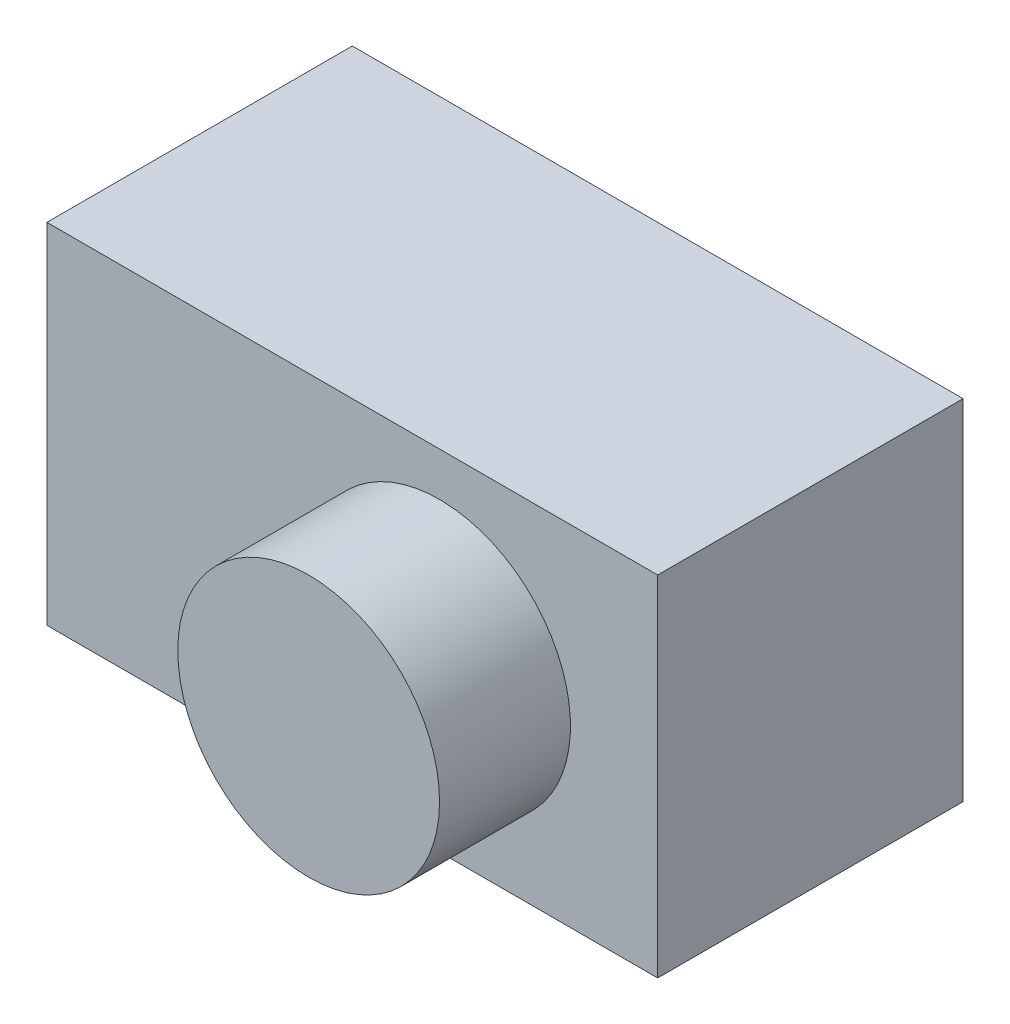
SolidWorks part; units mm, degrees
ref_plane "前视基准面" through (0, 0, 0) normal (0, 0, 1) x (1, 0, 0)
ref_plane "上视基准面" through (0, 0, 0) normal (0, 1, 0) x (1, 0, 0)
ref_plane "右视基准面" through (0, 0, 0) normal (1, 0, 0) x (0, 0, -1)
sketch "草图1" plane through (0, 0, 0) normal (0, 0, 1) x (1, 0, 0)
  line L1 (0, 0) -> (140, 0)
  line L2 (0, 0) -> (0, 80)
  line L3 (0, 80) -> (140, 80)
  line L4 (140, 0) -> (140, 80)
  dimension "D1" = 140
  dimension "D2" = 80
extrude "凸台-拉伸1" add sketch "草图1" along normal blind 70
sketch "草图2" plane through (0, 0, 70) normal (0, 0, 1) x (1, 0, 0)
  line L0 (0, 0) -> (140, 0) construction
  line L1 (140, 0) -> (140, 80) construction
  circle A0 centre (90, 40) radius 30
  dimension "D3" = 60
  dimension "D1" = 40
  dimension "D2" = 50
extrude "凸台-拉伸2" add sketch "草图2" along normal blind 30
